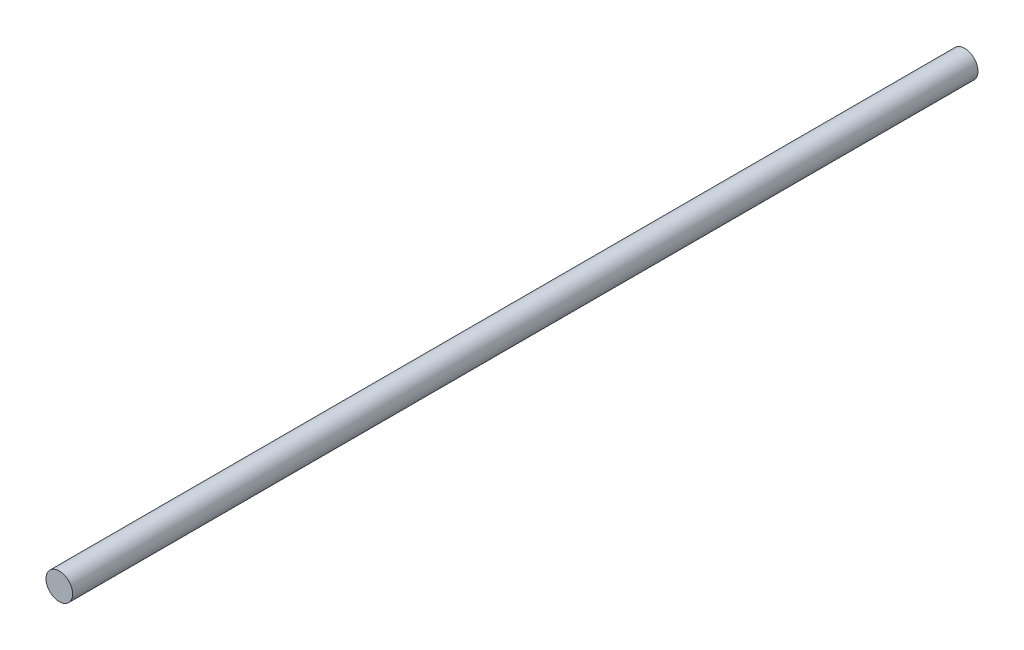
SolidWorks part; units mm, degrees
ref_plane "Front Plane" through (0, 0, 0) normal (0, 0, 1) x (1, 0, 0)
ref_plane "Top Plane" through (0, 0, 0) normal (0, 1, 0) x (1, 0, 0)
ref_plane "Right Plane" through (0, 0, 0) normal (1, 0, 0) x (0, 0, -1)
sketch "Sketch1" plane through (0, 0, 0) normal (0, 0, 1) x (1, 0, 0)
  circle A0 centre (0, 0) radius 2.5
  dimension "D1" = 5
extrude "Boss-Extrude1" add sketch "Sketch1" along normal blind 170 contours A0
